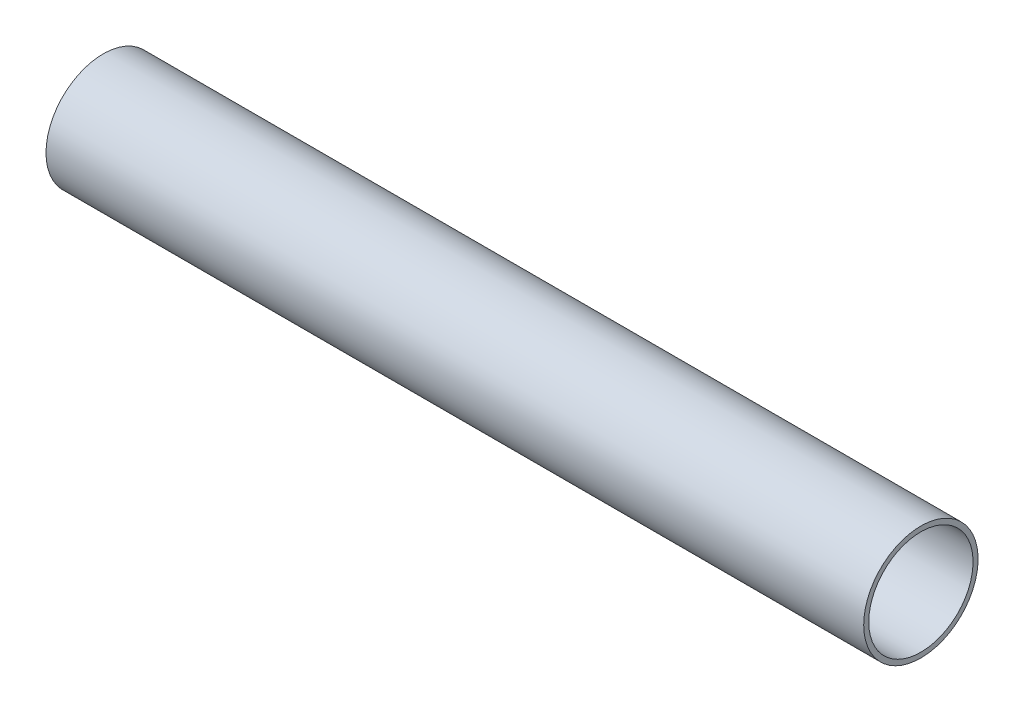
SolidWorks part; units mm, degrees
ref_plane "Front Plane" through (0, 0, 0) normal (0, 0, 1) x (1, 0, 0)
ref_plane "Top Plane" through (0, 0, 0) normal (0, 1, 0) x (1, 0, 0)
ref_plane "Right Plane" through (0, 0, 0) normal (1, 0, 0) x (0, 0, -1)
sketch "Sketch1" plane through (0, 0, 0) normal (0, 0, 1) x (1, 0, 0)
  line L0 (0, 0) -> (110.3138, 0) construction
  line L2 (0, -15.5) -> (243, -15.5)
  line L3 (0, -15.5) -> (0, -17)
  line L4 (0, -17) -> (243, -17)
  line L5 (243, -15.5) -> (243, -17)
  point P7 (0, 0)
  dimension "D1" = 15.5
  dimension "D2" = 17
  dimension "D3" = 243
revolve "Revolve1" add sketch "Sketch1" angle 360 about L0
